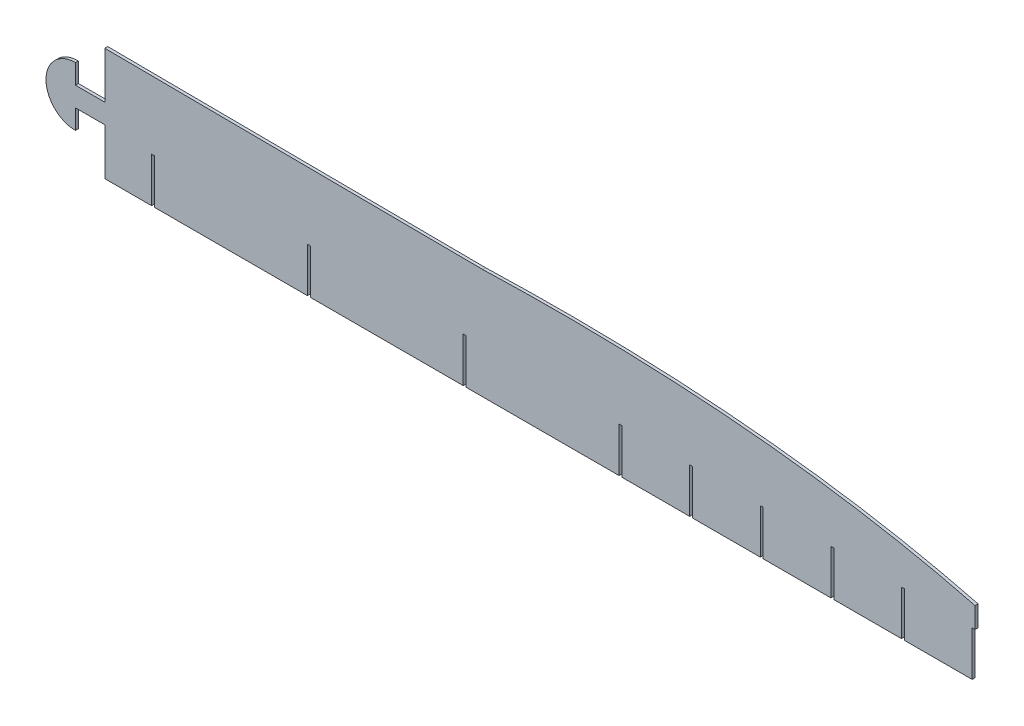
SolidWorks part; units mm, degrees
ref_plane "Front Plane" through (0, 0, 0) normal (0, 0, 1) x (1, 0, 0)
ref_plane "Top Plane" through (0, 0, 0) normal (0, 1, 0) x (1, 0, 0)
ref_plane "Right Plane" through (0, 0, 0) normal (1, 0, 0) x (0, 0, -1)
sketch "Model" plane through (0, 0, 0) normal (0, 0, 1) x (1, 0, 0)
  line L0 (1160.2, 315.6796) -> (1160.2, 268.0527)
  line L1 (1130.2, 268.0527) -> (1160.2, 268.0527)
  line L2 (1130.2, 288.0527) -> (1130.2, 268.0527)
  line L3 (1130.2, 248.0527) -> (1130.2, 228.0527)
  line L4 (1160.2, 248.0527) -> (1130.2, 248.0527)
  line L5 (1160.2, 248.0527) -> (1160.2, 200.4227)
  line L6 (1160.2, 200.4227) -> (1207.901, 200.4227)
  line L7 (1207.901, 245.9797) -> (1207.901, 200.4227)
  line L8 (1210.901, 245.9797) -> (1207.901, 245.9797)
  line L9 (1210.901, 200.4227) -> (1210.901, 245.9797)
  line L10 (1210.901, 200.4227) -> (1366.901, 200.4227)
  line L11 (1366.901, 245.9797) -> (1366.901, 200.4227)
  line L12 (1369.901, 245.9797) -> (1366.901, 245.9797)
  line L13 (1369.901, 200.4227) -> (1369.901, 245.9797)
  line L14 (1369.901, 200.4227) -> (1525.901, 200.4227)
  line L15 (1525.901, 245.9797) -> (1525.901, 200.4227)
  line L16 (1528.901, 245.9797) -> (1525.901, 245.9797)
  line L17 (1528.901, 200.4227) -> (1528.901, 245.9797)
  line L18 (1528.901, 200.4227) -> (1684.901, 200.4227)
  line L19 (1684.901, 245.9797) -> (1684.901, 200.4227)
  line L20 (1687.901, 245.9797) -> (1684.901, 245.9797)
  line L21 (1687.901, 200.4227) -> (1687.901, 245.9797)
  line L22 (1687.901, 200.4227) -> (1756.9435, 200.4227)
  line L23 (1756.9435, 245.9797) -> (1756.9435, 200.4227)
  line L24 (1759.9435, 245.9797) -> (1756.9435, 245.9797)
  line L25 (1759.9435, 200.4227) -> (1759.9435, 245.9797)
  line L26 (1759.9435, 200.4227) -> (1828.986, 200.4227)
  line L27 (1828.986, 245.9797) -> (1828.986, 200.4227)
  line L28 (1831.986, 245.9797) -> (1828.986, 245.9797)
  line L29 (1831.986, 200.4227) -> (1831.986, 245.9797)
  line L30 (1831.986, 200.4227) -> (1901.0286, 200.4227)
  line L31 (1901.0286, 245.9797) -> (1901.0286, 200.4227)
  line L32 (1904.0286, 245.9797) -> (1901.0286, 245.9797)
  line L33 (1904.0286, 200.4227) -> (1904.0286, 245.9797)
  line L34 (1904.0286, 200.4227) -> (1973.0711, 200.4227)
  line L35 (1973.0711, 245.9797) -> (1973.0711, 200.4227)
  line L36 (1976.0711, 245.9797) -> (1973.0711, 245.9797)
  line L37 (1976.0711, 200.4227) -> (1976.0711, 245.9797)
  line L38 (1976.0711, 200.4227) -> (2045.1136, 200.4227)
  line L39 (2045.1136, 245.9797) -> (2045.1136, 200.4227)
  line L40 (2048.1136, 245.9797) -> (2045.1136, 245.9797)
  line L41 (2048.1136, 267.2367) -> (2048.1136, 245.9797)
  arc A0 (1130.2, 288.0527) -> (1130.2, 228.0527) centre (1130.2, 258.0527) ccw
  spline S0 degree 3 poles (1545.731, 313) (1417.2198, 313.7868) (1288.7096, 314.6867) (1160.2, 315.6796) knots 0 0 0 0 1 1 1 1
  spline S1 degree 3 poles (2048.1136, 267.2367) (1921.1161, 299.876) (1758.3765, 319.6381) (1545.731, 313) knots 0.571508 0.571508 0.571508 0.571508 1 1 1 1
extrude "Boss-Extrude1" add sketch "Model" along normal blind 3
